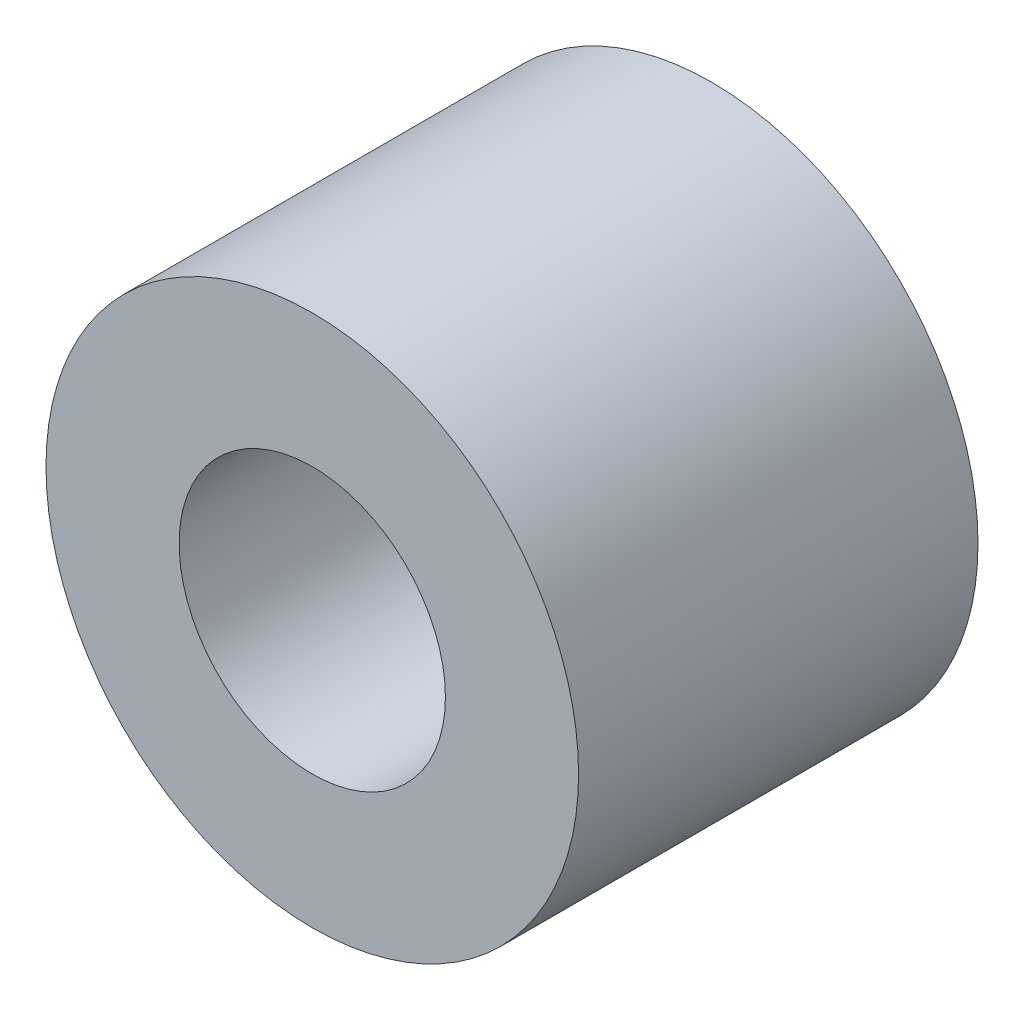
SolidWorks part; units mm, degrees
ref_plane "Front Plane" through (0, 0, 0) normal (0, 0, 1) x (1, 0, 0)
ref_plane "Top Plane" through (0, 0, 0) normal (0, 1, 0) x (1, 0, 0)
ref_plane "Right Plane" through (0, 0, 0) normal (1, 0, 0) x (0, 0, -1)
sketch "Sketch1" plane through (0, 0, 0) normal (0, 0, 1) x (1, 0, 0)
  circle A0 centre (6, 6) radius 6
  circle A1 centre (6, 6) radius 3
  dimension "D1" = 6
  dimension "D2" = 12
extrude "Profile" add sketch "Sketch1" along normal blind 9
equation "\"Profile_Depth\"= 9mm"
equation "\"D1@Profile\" = \"Profile_Depth\""
equation "\"Profile_Sketch_1\"= 6mm"
equation "\"D1@Sketch1\" = \"Profile_Sketch_1\""
equation "\"Profile_Sketch_2\"= 12mm"
equation "\"D2@Sketch1\" = \"Profile_Sketch_2\""
equation "\"EnvelopeWidth\"= 12mm"
equation "\"EnvelopeHeight\"= 12mm"
